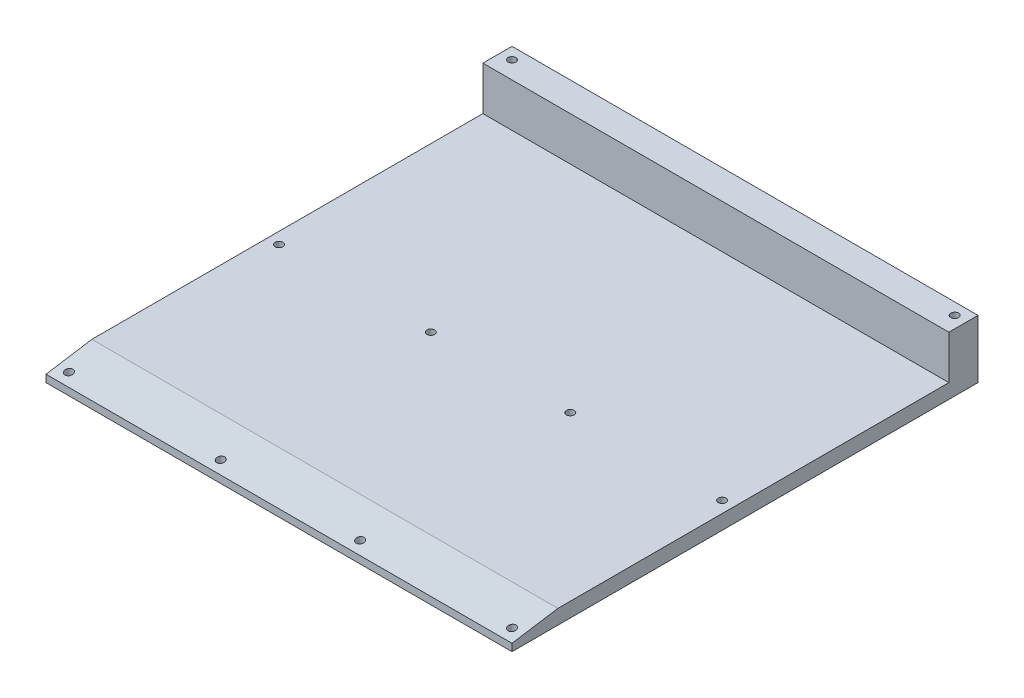
SolidWorks part; units mm, degrees
ref_plane "Front Plane" through (0, 0, 0) normal (0, 0, 1) x (1, 0, 0)
ref_plane "Top Plane" through (0, 0, 0) normal (0, 1, 0) x (1, 0, 0)
ref_plane "Right Plane" through (0, 0, 0) normal (1, 0, 0) x (0, 0, -1)
sketch "Sketch1" plane through (0, 0, 0) normal (0, 1, 0) x (1, 0, 0)
  line L1 (0, 0) -> (76.2, 0)
  line L2 (0, 0) -> (0, 101.6)
  line L3 (0, 101.6) -> (76.2, 101.6)
  line L4 (76.2, 0) -> (76.2, 101.6)
  line L5 (76.2, 101.6) -> (0, 101.6)
  line L6 (76.2, 101.6) -> (76.2, 203.2)
  line L7 (76.2, 203.2) -> (0, 203.2)
  line L8 (0, 101.6) -> (0, 203.2)
  dimension "D1" = 101.6
  dimension "D2" = 76.2
  dimension "D3" = 101.6
extrude "Boss-Extrude1" add sketch "Sketch1" along normal blind 6.35 contours L1 L4 L3 L2 | L8 L3 L6 L7
ref_plane "Plane4" through (0, 6.35, 0) normal (0, 1, 0) x (1, 0, 0)
sketch "Sketch2" plane through (0, 6.35, 0) normal (0, 1, 0) x (1, 0, 0)
  line L0 (38.1, 0) -> (38.1, 68.5972) construction
  line L2 (0, 50.8) -> (66.4895, 50.8) construction
  line L4 (-53.2921, 101.6) -> (129.9514, 101.6) construction
  line L5 (0, 0) -> (76.2, 0) construction
  line L8 (0, 0) -> (0, 203.2) construction
  line L9 (76.2, 0) -> (76.2, 203.2) construction
  line L10 (76.2, 203.2) -> (0, 203.2) construction
  circle A0 centre (5, 96.6) radius 1.7
  circle A1 centre (71.2, 96.6) radius 1.7
  circle A2 centre (71.2, 5) radius 1.7
  circle A3 centre (5, 5) radius 1.7
  circle A4 centre (71.12, 198.12) radius 1.7
  point P2 (33.2447, 50.8)
  point P3 (38.1, 34.2986)
  dimension "D1" = 3.4
  dimension "D8" = 3.4
  dimension "D2" = 5
  dimension "D3" = 5
  dimension "D4" = 50.8
  dimension "D5" = 50.8
  dimension "D6" = 5.08
  dimension "D7" = 5.08
extrude "Cut-Extrude1" cut sketch "Sketch2" against normal through all contours A0 | A1 | A3 | A2 | A4
ref_plane "Plane1" through (15, 0, 0) normal (-1, 0, 0) x (0, 0, 1)
ref_plane "Plane2" through (61.2, 0, 0) normal (1, 0, 0) x (0, 0, -1)
sketch "Sketch3" plane through (0, 0, 0) normal (-1, 0, 0) x (0, 0, 1)
  line L0 (-101.6, 6.35) -> (-20, 6.35)
  line L1 (0, 3.175) -> (0, 0)
  line L2 (-20, 6.35) -> (0, 3.175)
  line L3 (-20, 6.35) -> (0, 6.35)
  line L4 (0, 6.35) -> (0, 3.175)
  point P1 (0, 6.35)
  dimension "D1" = 20
  dimension "D2" = 3.175
extrude "Cut-Extrude2" cut sketch "Sketch3" against normal through all
ref_plane "Plane3" through (-25.4, 0, 0) normal (-1, 0, 0) x (0, 0, 1)
mirror "Mirror3" about plane through (-25.4, 0, 0) normal (-1, 0, 0) of bodies 103
sketch "Sketch5" plane through (-50.8, 0, 0) normal (1, 0, 0) x (0, 0, -1)
  line L0 (20, 6.35) -> (203.2, 6.35)
  line L1 (203.2, 6.35) -> (203.2, 0)
  line L2 (203.2, 0) -> (0, 0)
  line L3 (0, 0) -> (0, 3.175)
  line L4 (0, 3.175) -> (20, 6.35)
  line L5 (0, 0) -> (203.2, 0) construction
  line L6 (203.2, 6.35) -> (203.2, 0) construction
  line L7 (41.91, 6.35) -> (-41.91, 6.35) construction
  line L9 (20, 6.35) -> (0, 3.175) construction
extrude "Boss-Extrude2" add sketch "Sketch5" along normal up to surface (50.8 mm away) up to face at (0, 3.175, -85.28)
sketch "Sketch8" plane through (0, 6.35, 0) normal (0, 1, 0) x (1, 0, 0)
  line L0 (76.2, 20) -> (76.2, 203.2) construction
  line L1 (-127, 203.2) -> (76.2, 203.2)
  line L2 (-127, 203.2) -> (-127, 190.5)
  line L3 (-127, 190.5) -> (76.2, 190.5)
  line L4 (76.2, 203.2) -> (76.2, 190.5)
  line L5 (-25.4, 203.2) -> (-25.4, 190.5) construction
  circle A1 centre (-121.92, 198.12) radius 1.7
  circle A2 centre (71.12, 198.12) radius 1.7
  dimension "D2" = 3.4
  dimension "D1" = 12.7
extrude "Boss-Extrude5" add sketch "Sketch8" along normal blind 19.05
